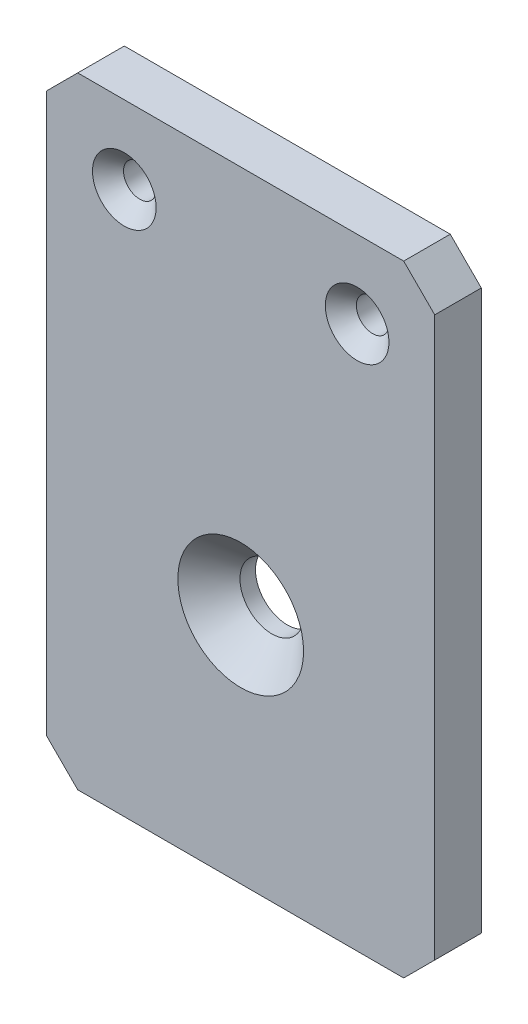
SolidWorks part; units mm, degrees
ref_plane "前视基准面" through (0, 0, 0) normal (0, 0, 1) x (1, 0, 0)
ref_plane "上视基准面" through (0, 0, 0) normal (0, 1, 0) x (1, 0, 0)
ref_plane "右视基准面" through (0, 0, 0) normal (1, 0, 0) x (0, 0, -1)
sketch "草图1" plane through (0, 0, 0) normal (0, 0, 1) x (1, 0, 0)
  line L1 (25, -30) -> (-25, -30)
  line L2 (25, -30) -> (25, 50)
  line L3 (25, 50) -> (-25, 50)
  line L4 (-25, -30) -> (-25, 50)
  line L5 (25, -30) -> (-25, 50) construction
  line L6 (25, 50) -> (-25, -30) construction
  line L7 (-15, 40) -> (15, 40) construction
  circle A0 centre (0, 0) radius 4.1
  circle A3 centre (-15, 40) radius 2.1
  circle A4 centre (15, 40) radius 2.1
  point P3 (0, 10)
  point P17 (0, 40)
  point P18 (0, 50)
  dimension "D1" = 50
  dimension "D2" = 8.2
  dimension "D3" = 30
  dimension "D6" = 25
  dimension "D9" = 10
  dimension "D4" = 10
  dimension "D5" = 4.2
  dimension "D10" = 10
extrude "凸台-拉伸1" add sketch "草图1" along normal mid plane 6
chamfer "倒角2" distance 4 angle 45 5 edges at (-25, 50, 0) (25, -30, 0) (-25, -30, 0) (4.1, 0, 3) (25, 50, 0)
chamfer "倒角3" distance 2 angle 45 2 edges at (-12.9, 40, 3) (17.1, 40, 3)
